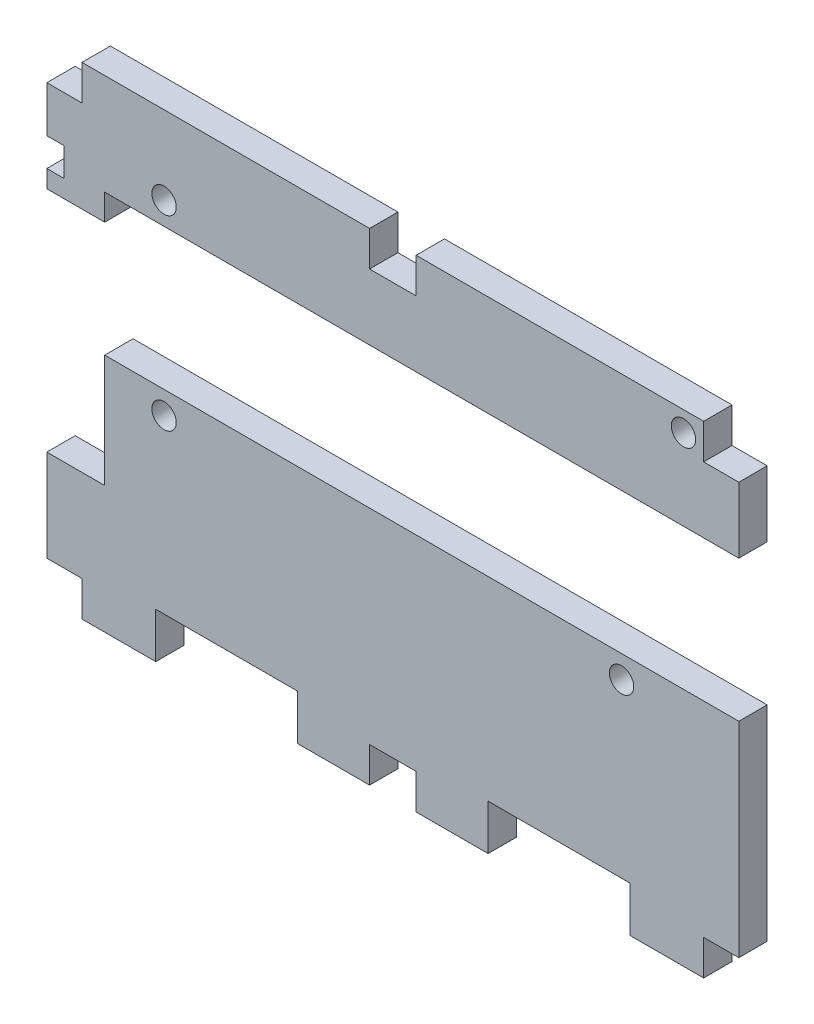
SolidWorks part; units mm, degrees
ref_plane "前视基准面" through (0, 0, 0) normal (0, 0, 1) x (1, 0, 0)
ref_plane "上视基准面" through (0, 0, 0) normal (0, 1, 0) x (1, 0, 0)
ref_plane "右视基准面" through (0, 0, 0) normal (1, 0, 0) x (0, 0, -1)
other "Configuration Table"
sketch "草图1" plane through (0, 0, 0) normal (0, 0, 1) x (1, 0, 0)
  line L1 (-61, 42.5) -> (61, 42.5)
  line L2 (-61, 42.5) -> (-61, -42.5)
  line L3 (-61, -42.5) -> (61, -42.5)
  line L4 (61, 42.5) -> (61, -42.5)
  line L5 (0, -42.5) -> (0, 42.5) construction
  line L6 (-61, 0) -> (61, 0) construction
  point P0 (0, 0)
  dimension "D1" = 122
  dimension "D2" = 85
extrude "凸台-拉伸1" add sketch "草图1" along normal blind 5
sketch "草图2" plane through (0, 0, 5) normal (0, 0, 1) x (1, 0, 0)
  line L0 (61, 42.5) -> (-61, 42.5) construction
  line L1 (-4.1, 42.5) -> (4.1, 42.5)
  line L2 (-4.1, 42.5) -> (-4.1, 36.3)
  line L3 (-4.1, 36.3) -> (4.1, 36.3)
  line L4 (4.1, 42.5) -> (4.1, 36.3)
  line L5 (-61, 0) -> (61, 0) construction
  line L6 (-61, 42.5) -> (-54.8, 42.5)
  line L7 (-61, 42.5) -> (-61, 36.3)
  line L8 (-61, 36.3) -> (-54.8, 36.3)
  line L9 (-54.8, 42.5) -> (-54.8, 36.3)
  line L10 (61, 42.5) -> (54.8, 42.5)
  line L11 (61, 42.5) -> (61, 36.3)
  line L12 (61, 36.3) -> (54.8, 36.3)
  line L13 (54.8, 42.5) -> (54.8, 36.3)
  line L14 (-61, 42.5) -> (-61, -42.5) construction
  line L15 (61, -42.5) -> (61, 42.5) construction
  line L16 (61, -36.3) -> (54.8, -36.3)
  line L17 (54.8, -42.5) -> (54.8, -36.3)
  line L18 (61, -42.5) -> (54.8, -42.5)
  line L19 (61, -42.5) -> (61, -36.3)
  line L20 (-4.1, -36.3) -> (4.1, -36.3)
  line L21 (4.1, -42.5) -> (4.1, -36.3)
  line L22 (-4.1, -42.5) -> (4.1, -42.5)
  line L23 (-4.1, -42.5) -> (-4.1, -36.3)
  line L24 (-61, -36.3) -> (-54.8, -36.3)
  line L25 (-54.8, -42.5) -> (-54.8, -36.3)
  line L26 (-61, -42.5) -> (-54.8, -42.5)
  line L27 (-61, -42.5) -> (-61, -36.3)
  line L29 (-61, 20.1) -> (-50.8, 20.1)
  line L30 (-61, 20.1) -> (-61, -20.1)
  line L31 (-61, -20.1) -> (-50.8, -20.1)
  line L32 (-50.8, 20.1) -> (-50.8, -20.1)
  dimension "D1" = 8.2
  dimension "D2" = 6.2
  dimension "D3" = 4.1
  dimension "D4" = 6.2
  dimension "D5" = 6.2
  dimension "D6" = 6.2
  dimension "D7" = 6.2
  dimension "D8" = 10.2
  dimension "D9" = 40.2
  dimension "D10" = 20.1
extrude "切除-拉伸1" cut sketch "草图2" against normal blind 5
sketch "草图6" plane through (0, 0, 0) normal (0, 0, -1) x (-1, 0, 0)
  line L0 (-54.8, 42.5) -> (-54.8, 36.3) construction
  line L4 (-54.8, 42.5) -> (-4.1, 42.5) construction
  line L5 (4.1, 42.5) -> (54.8, 42.5) construction
  circle A0 centre (-51.244, 38.982) radius 2.15
  circle A1 centre (-40.322, -4.198) radius 2.15
  circle A2 centre (40.33, 28.695) radius 2.15
  circle A3 centre (40.331, -4.198) radius 2.15
  dimension "D1" = 4.3
  dimension "D2" = 3.556
  dimension "D3" = 3.518
  dimension "D4" = 43.18
  dimension "D5" = 14.478
  dimension "D6" = 80.653
  dimension "D7" = 46.698
  dimension "D8" = 32.893
  dimension "D9" = 95.13
extrude "切除-拉伸2" cut sketch "草图6" against normal blind 5
sketch "草图8" plane through (0, 0, 0) normal (0, 0, -1) x (-1, 0, 0)
  line L0 (-61, -36.3) -> (-61, 36.3) construction
  line L1 (-61, 24.695) -> (50.8, 24.695)
  line L2 (-61, 24.695) -> (-61, -0.198)
  line L3 (-61, -0.198) -> (50.8, -0.198)
  line L4 (50.8, 24.695) -> (50.8, -0.198)
  line L5 (50.8, -20.1) -> (50.8, 20.1) construction
  line L6 (-4.1, -42.5) -> (-54.8, -42.5) construction
  line L7 (-41.8, -34.5) -> (-16.8, -34.5)
  line L8 (-41.8, -34.5) -> (-41.8, -42.5)
  line L9 (-41.8, -42.5) -> (-16.8, -42.5)
  line L10 (-16.8, -34.5) -> (-16.8, -42.5)
  line L11 (54.8, -42.5) -> (4.1, -42.5) construction
  line L12 (16.8, -34.5) -> (41.8, -34.5)
  line L13 (16.8, -34.5) -> (16.8, -42.5)
  line L14 (16.8, -42.5) -> (41.8, -42.5)
  line L15 (41.8, -34.5) -> (41.8, -42.5)
  line L16 (54.8, -42.5) -> (54.8, -36.3) construction
  line L17 (-54.8, -36.3) -> (-54.8, -42.5) construction
  circle A0 centre (40.33, 28.695) radius 2.15 construction
  circle A1 centre (40.331, -4.198) radius 2.15 construction
  dimension "D1" = 4
  dimension "D2" = 4
  dimension "D3" = 25
  dimension "D4" = 25
  dimension "D5" = 13
  dimension "D6" = 13
  dimension "D7" = 8
  dimension "D8" = 8
extrude "切除-拉伸5" cut sketch "草图8" against normal blind 5
sketch "草图9" plane through (0, 0, 0) normal (0, 0, -1) x (-1, 0, 0)
  line L0 (61, 36.3) -> (61, 20.1) construction
  line L1 (61, 28.2) -> (58, 28.2)
  line L2 (61, 28.2) -> (61, 23.2)
  line L3 (61, 23.2) -> (58, 23.2)
  line L4 (58, 28.2) -> (58, 23.2)
  dimension "D1" = 3
  dimension "D2" = 5
extrude "切除-拉伸6" cut sketch "草图9" against normal blind 5
